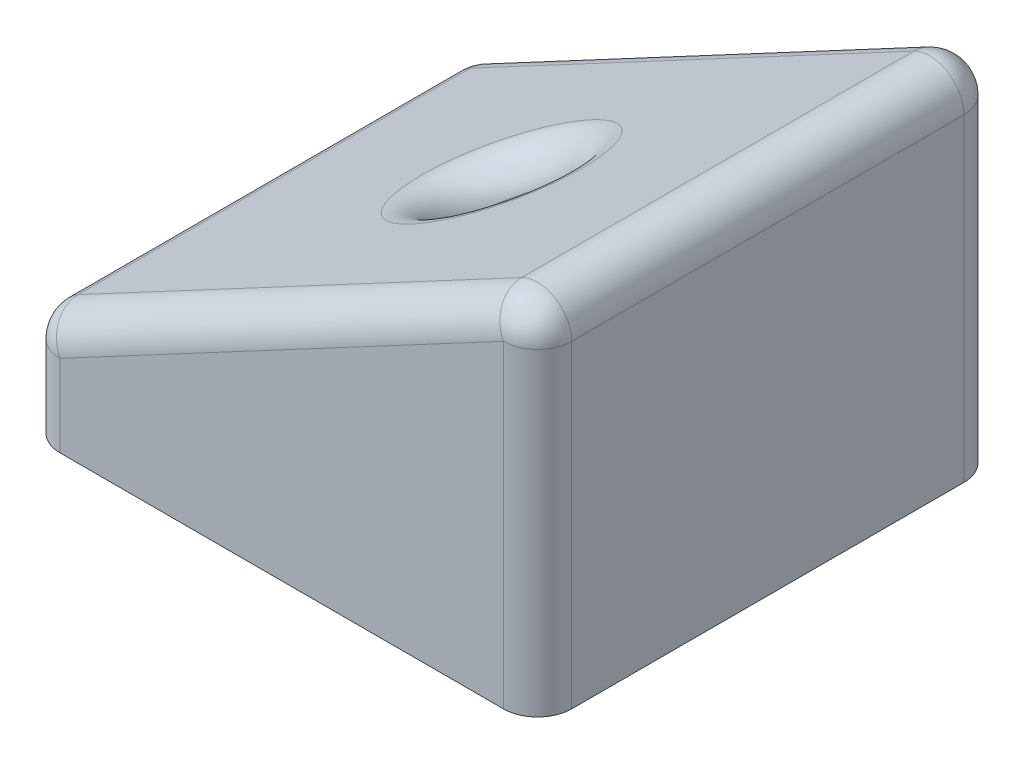
SolidWorks part; units mm, degrees
ref_plane "Front Plane" through (0, 0, 0) normal (0, 0, 1) x (1, 0, 0)
ref_plane "Top Plane" through (0, 0, 0) normal (0, 1, 0) x (1, 0, 0)
ref_plane "Right Plane" through (0, 0, 0) normal (1, 0, 0) x (0, 0, -1)
sketch "Sketch1" plane through (0, 0, 0) normal (0, 1, 0) x (1, 0, 0)
  line L1 (0, 0) -> (30, 0)
  line L2 (0, 0) -> (0, -27)
  line L3 (0, -27) -> (30, -27)
  line L4 (30, 0) -> (30, -27)
extrude "Boss-Extrude1" add sketch "Sketch1" along normal blind 22
sketch "Sketch2" plane through (0, 0, 27) normal (0, 0, 1) x (1, 0, 0)
  line L0 (0, 0) -> (0, 6) construction
  line L1 (0, 22) -> (0, 0) construction
  line L2 (0, 6) -> (0, 22)
  line L3 (0, 6) -> (30, 22)
  line L4 (0, 22) -> (30, 22)
extrude "Cut-Extrude1" cut sketch "Sketch2" against normal through all
sketch "Sketch3" plane through (-2.4913, 4.6713, 0) normal (-0.4706, 0.8824, 0) x (0.8824, 0.4706, 0)
  line L0 (2.8235, -27) -> (36.8235, 0) construction
  line L1 (2.8235, 0) -> (36.8235, -27) construction
  line L2 (22.3941, -19.0149) -> (25.6273, -13.4149)
  line L3 (19.0365, -19.0149) -> (22.3941, -19.0149)
  line L4 (19.0365, -19.0149) -> (15.679, -19.0149)
  line L5 (15.679, -19.0149) -> (12.4458, -13.4149)
  line L6 (15.679, -7.8149) -> (12.4458, -13.4149)
  line L7 (22.3941, -7.8149) -> (25.6273, -13.4149)
  line L8 (19.0365, -7.8149) -> (22.3941, -7.8149)
  line L9 (19.0365, -7.8149) -> (15.679, -7.8149)
  line L10 (18.8205, -0.0009) -> (19.1268, -26.9991) construction
  line L11 (39.9723, -13.2618) -> (-2.025, -13.7382) construction
  line L12 (19.0561, -0.0003) -> (19.0561, -27.2604) construction
extrude "Cut-Extrude2" cut sketch "Sketch3" against normal through all
sketch "Sketch4" plane through (-2.4913, 4.6713, 0) normal (-0.4706, 0.8824, 0) x (0.8824, 0.4706, 0)
  line L0 (25.6273, -13.4149) -> (12.4458, -13.4149) construction
  circle A0 centre (19.0365, -13.4149) radius 6.9606
  circle A1 centre (19.0365, -13.4149) radius 3.3
extrude "Boss-Extrude2" add sketch "Sketch4" against normal blind 8
sketch "Sketch5" plane through (-2.4913, 4.6713, 0) normal (-0.4706, 0.8824, 0) x (0.8824, 0.4706, 0)
  line L0 (15.7365, -13.4149) -> (15.7365, 0) construction
  line L1 (2.8235, 0) -> (36.8235, 0) construction
  line L2 (22.3365, -13.4149) -> (22.3365, 0) construction
  circle A0 centre (19.0365, -13.4149) radius 3.3 construction
fillet "Fillet2" radius 2 9 edges at (11.3938, 12.0767, 13.4149) (0, 6, 13.5) (15, 14, 0) (30, 22, 13.5) (15, 14, 27) (0, 3, 0) (0, 3, 27) (30, 11, 27) (30, 11, 0)
